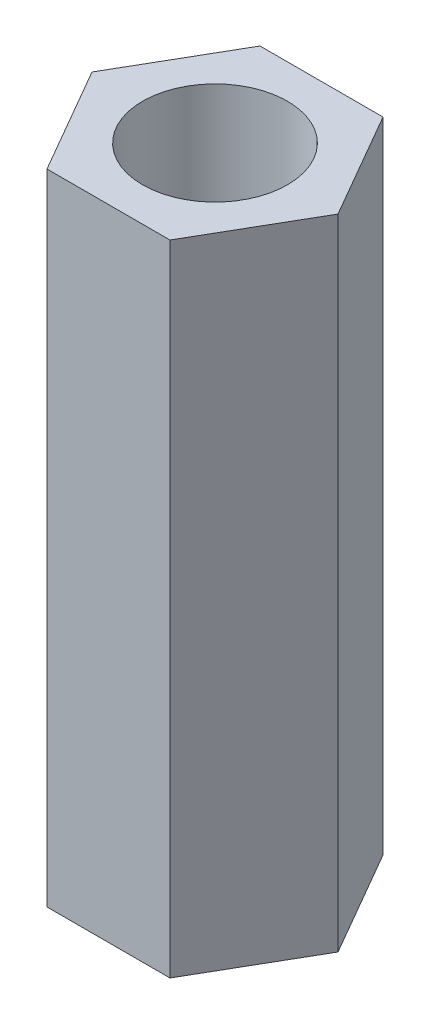
SolidWorks part; units mm, degrees
ref_plane "前视基准面" through (0, 0, 0) normal (0, 0, 1) x (1, 0, 0)
ref_plane "上视基准面" through (0, 0, 0) normal (0, 1, 0) x (1, 0, 0)
ref_plane "右视基准面" through (0, 0, 0) normal (1, 0, 0) x (0, 0, -1)
sketch "草图1" plane through (0, 0, 0) normal (0, 1, 0) x (1, 0, 0)
  line L1 (2.8868, 0) -> (1.4434, 2.5)
  line L2 (1.4434, 2.5) -> (-1.4434, 2.5)
  line L3 (-1.4434, 2.5) -> (-2.8868, 0)
  line L4 (-2.8868, 0) -> (-1.4434, -2.5)
  line L5 (-1.4434, -2.5) -> (1.4434, -2.5)
  line L6 (1.4434, -2.5) -> (2.8868, 0)
  circle A0 centre (0, 0) radius 1.7
  circle A1 centre (0, 0) radius 2.5 construction
  dimension "D1" = 3.4
  dimension "D2" = 5
extrude "凸台-拉伸1" add sketch "草图1" along normal blind 15
equation "\"h2\"= 15'铜柱的长度"
equation "\"D1@凸台-拉伸1\"=\"h2\""
equation "\"d\"= 3'螺丝直径(有补偿)"
equation "\"D1@草图1\"=\"d\"+0.4"
equation "\"h1\"= 9.6'铜柱的长度"
equation "\"h3\"= 30'铜柱的长度"
